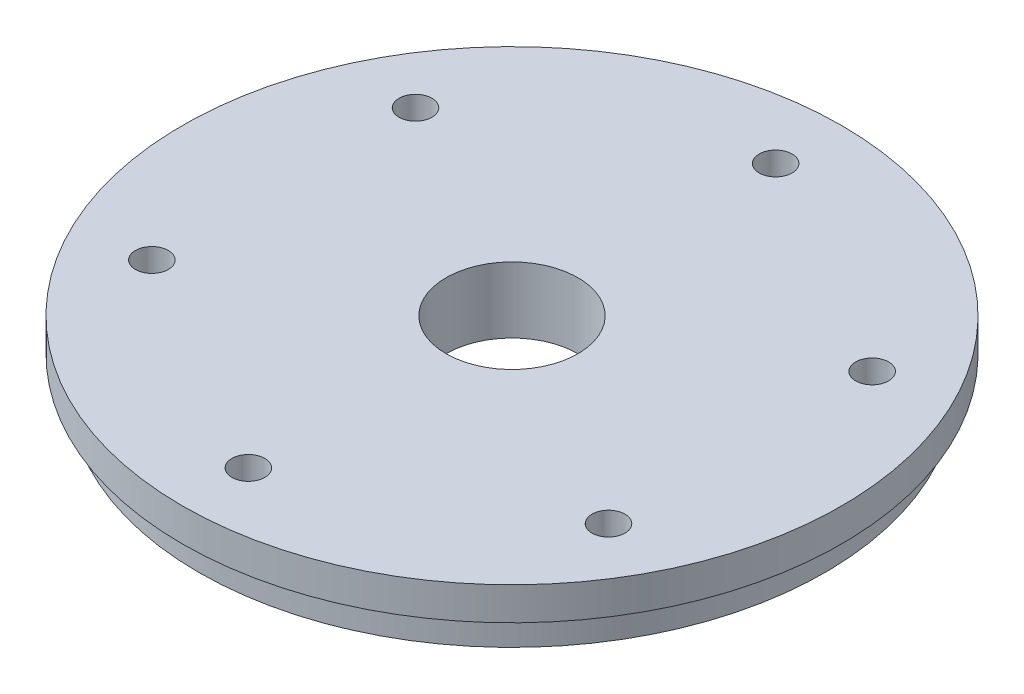
SolidWorks part; units mm, degrees
ref_plane "Front Plane" through (0, 0, 0) normal (0, 0, 1) x (1, 0, 0)
ref_plane "Top Plane" through (0, 0, 0) normal (0, 1, 0) x (1, 0, 0)
ref_plane "Right Plane" through (0, 0, 0) normal (1, 0, 0) x (0, 0, -1)
sketch "Sketch1" plane through (0, 0, 0) normal (0, 1, 0) x (1, 0, 0)
  circle A0 centre (0, 0) radius 30.1625
  dimension "D1" = 60.325
extrude "Boss-Extrude1" add sketch "Sketch1" along normal blind 3.175
sketch "Sketch2" plane through (0, 3.175, 0) normal (0, 1, 0) x (1, 0, 0)
  circle A0 centre (0, 0) radius 31.75
  circle A1 centre (0, 0) radius 30.1625 construction
  dimension "D1" = 1.5875
extrude "Boss-Extrude2" add sketch "Sketch2" along normal blind 3.175
sketch "Sketch3" plane through (0, 6.35, 0) normal (0, 1, 0) x (1, 0, 0)
  circle A0 centre (0, 25.4) radius 1.5875
  circle A1 centre (21.997, 12.7) radius 1.5875
  circle A2 centre (21.997, -12.7) radius 1.5875
  circle A3 centre (0, -25.4) radius 1.5875
  circle A4 centre (-21.997, -12.7) radius 1.5875
  circle A5 centre (-21.997, 12.7) radius 1.5875
  circle A6 centre (0, 0) radius 6.35
  point P16 (0, 0)
  dimension "D1" = 3.175
  dimension "D4" = 12.7
  dimension "D2" = 25.4
  dimension "D3" = 6
extrude "Cut-Extrude1" cut sketch "Sketch3" against normal through all
